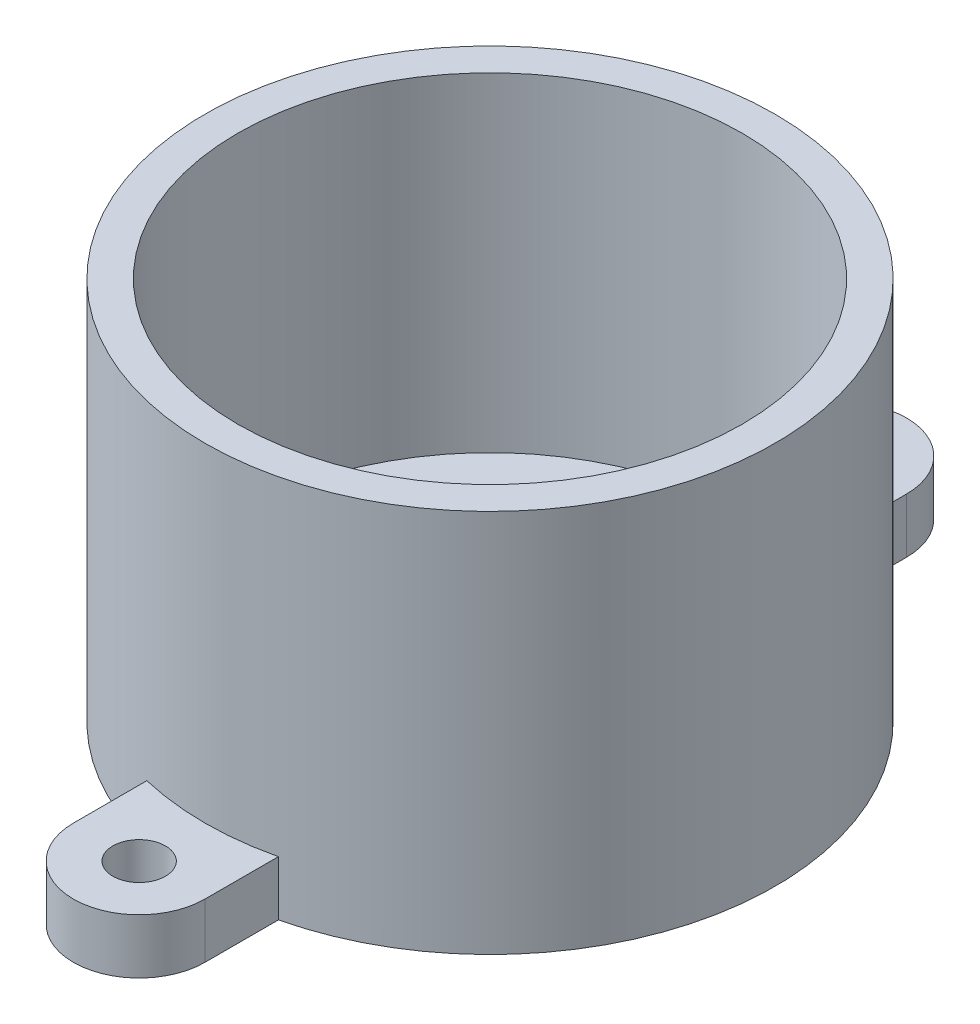
SolidWorks part; units mm, degrees
ref_plane "Front Plane" through (0, 0, 0) normal (0, 0, 1) x (1, 0, 0)
ref_plane "Top Plane" through (0, 0, 0) normal (0, 1, 0) x (1, 0, 0)
ref_plane "Right Plane" through (0, 0, 0) normal (1, 0, 0) x (0, 0, -1)
sketch "Sketch1" plane through (0, 0, 0) normal (0, 1, 0) x (1, 0, 0)
  circle A0 centre (0, 0) radius 13
  dimension "D1" = 26
extrude "Boss-Extrude1" add sketch "Sketch1" along normal blind 2.5
sketch "Sketch2" plane through (0, 0, 0) normal (0, 1, 0) x (1, 0, 0)
  circle A1 centre (0, 0) radius 13 construction
  circle A2 centre (0, 0) radius 11.5
  circle A3 centre (0, 0) radius 11.5
  circle A4 centre (0, 0) radius 13
  dimension "D1" = 1.5
extrude "Boss-Extrude2" add sketch "Sketch2" along normal blind 15 from surface at 2.5 starting at face at (0, 2.5, 13)
sketch "Sketch3" plane through (0, 0, 0) normal (0, 1, 0) x (1, 0, 0)
  circle A0 centre (0, 0) radius 5.5
  dimension "D1" = 11
extrude "Cut-Extrude1" cut sketch "Sketch3" against normal blind 1.2 from surface at 2.5 starting at face at (0, 2.5, 11.5)
sketch "Sketch4" plane through (0, 0, 0) normal (0, 1, 0) x (1, 0, 0)
  circle A0 centre (0, 0) radius 8.5 construction
  circle A1 centre (0, 8.5) radius 1.2
  circle A2 centre (7.3612, -4.25) radius 1.2
  circle A3 centre (-7.3612, -4.25) radius 1.2
  circle A4 centre (0, 0) radius 2
  point P11 (0, 0)
  dimension "D1" = 17
  dimension "D2" = 2.4
  dimension "D4" = 4
  dimension "D3" = 3
extrude "Cut-Extrude2" cut sketch "Sketch4" against normal through all both and the other way through all
sketch "Sketch5" plane through (0, 0, 0) normal (0, 1, 0) x (1, 0, 0)
  line L0 (-17.4895, 0) -> (16.6201, 0) construction
  line L1 (0, 0) -> (0, 20.2843) construction
  line L2 (-3, 12.6491) -> (-3, 16)
  line L3 (3, 16) -> (3, 12.6491)
  line L4 (3, -16) -> (3, -12.6491)
  line L5 (-3, -12.6491) -> (-3, -16)
  circle A0 centre (0, 0) radius 13 construction
  arc A1 (3, 12.6491) -> (-3, 12.6491) centre (0, 0) ccw
  arc A2 (-3, 16) -> (0, 19) centre (0, 16) cw
  arc A3 (0, 19) -> (3, 16) centre (0, 16) cw
  circle A4 centre (0, 16) radius 1.2
  circle A5 centre (0, -16) radius 1.2
  arc A6 (0, -19) -> (3, -16) centre (0, -16) ccw
  arc A7 (-3, -16) -> (0, -19) centre (0, -16) ccw
  arc A8 (3, -12.6491) -> (-3, -12.6491) centre (0, 0) cw
  dimension "D1" = 6
  dimension "D3" = 2.4
  dimension "D2" = 19
extrude "Boss-Extrude3" add sketch "Sketch5" along normal blind 2.5
